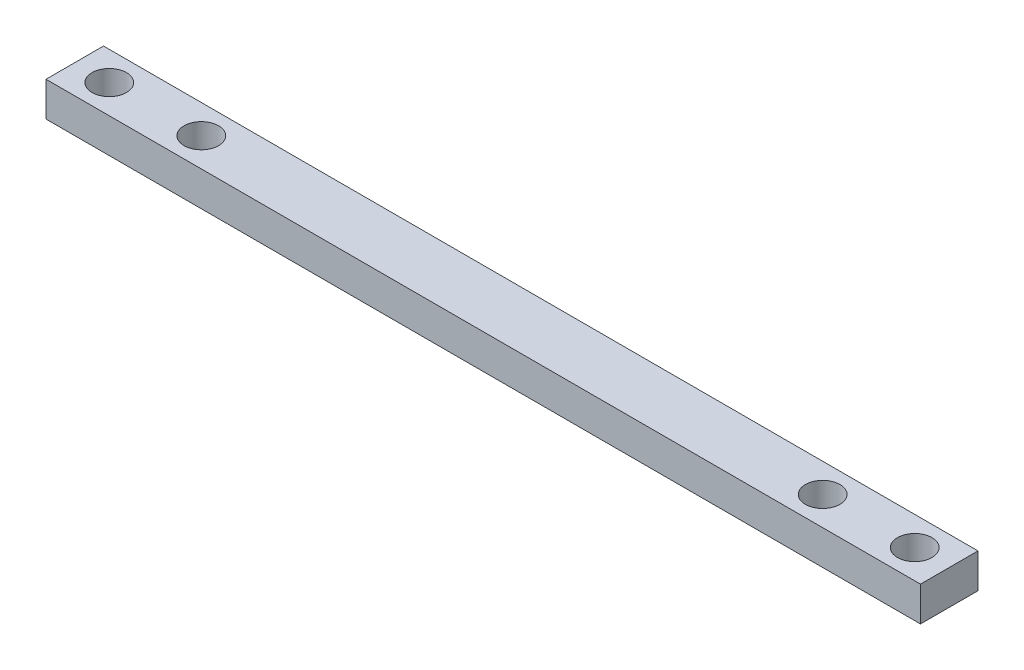
SolidWorks part; units mm, degrees
ref_plane "Front Plane" through (0, 0, 0) normal (0, 0, 1) x (1, 0, 0)
ref_plane "Top Plane" through (0, 0, 0) normal (0, 1, 0) x (1, 0, 0)
ref_plane "Right Plane" through (0, 0, 0) normal (1, 0, 0) x (0, 0, -1)
sketch "Sketch1" plane through (0, 0, 0) normal (0, 1, 0) x (1, 0, 0)
  line L1 (-38, -2.5) -> (38, -2.5)
  line L2 (-38, -2.5) -> (-38, 2.5)
  line L3 (-38, 2.5) -> (38, 2.5)
  line L4 (38, -2.5) -> (38, 2.5)
  line L5 (0, 2.5) -> (0, -2.5) construction
  line L6 (-38, 0) -> (38, 0) construction
  circle A0 centre (-35, 0) radius 1.5
  circle A1 centre (-27, 0) radius 1.5
  circle A2 centre (35, 0) radius 1.5
  circle A3 centre (27, 0) radius 1.5
  point P0 (0, 0)
  dimension "D4" = 3
  dimension "D5" = 3
  dimension "D1" = 76
  dimension "D2" = 5
  dimension "D3" = 3
  dimension "D6" = 8
extrude "Boss-Extrude1" add sketch "Sketch1" along normal blind 3
